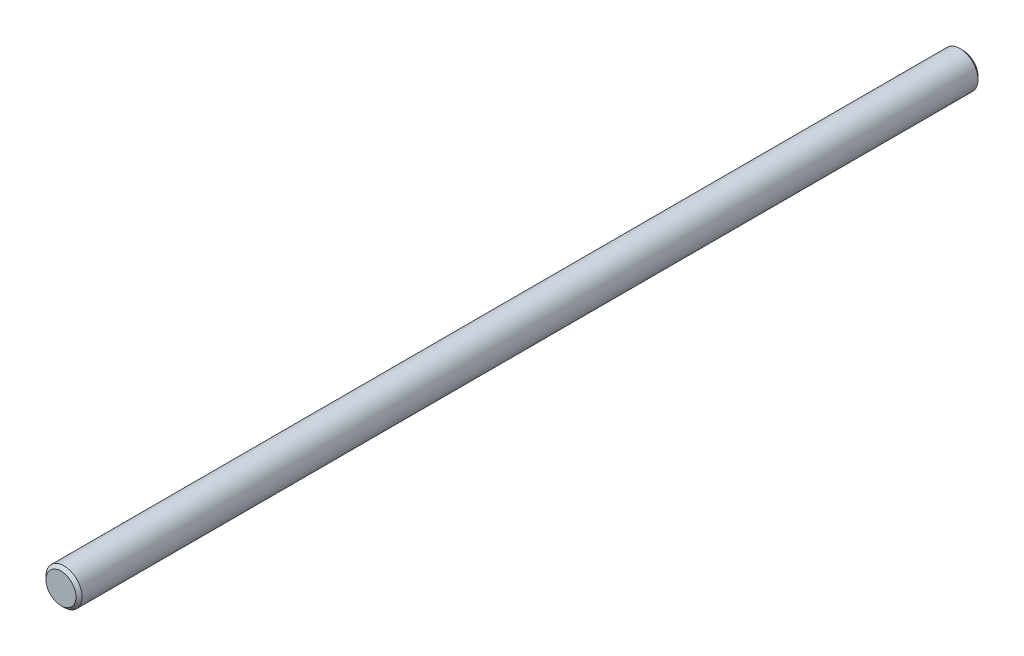
SolidWorks part; units mm, degrees
ref_plane "Front Plane" through (0, 0, 0) normal (0, 0, 1) x (1, 0, 0)
ref_plane "Top Plane" through (0, 0, 0) normal (0, 1, 0) x (1, 0, 0)
ref_plane "Right Plane" through (0, 0, 0) normal (1, 0, 0) x (0, 0, -1)
sketch "Sketch1" plane through (0, 0, 0) normal (0, 0, 1) x (1, 0, 0)
  circle A0 centre (0, 0) radius 6
  dimension "D1" = 12
extrude "Boss-Extrude1" add sketch "Sketch1" along normal mid plane 300
chamfer "Chamfer1" distance 1 angle 45 2 edges at (6, 0, -150) (6, 0, 150)
